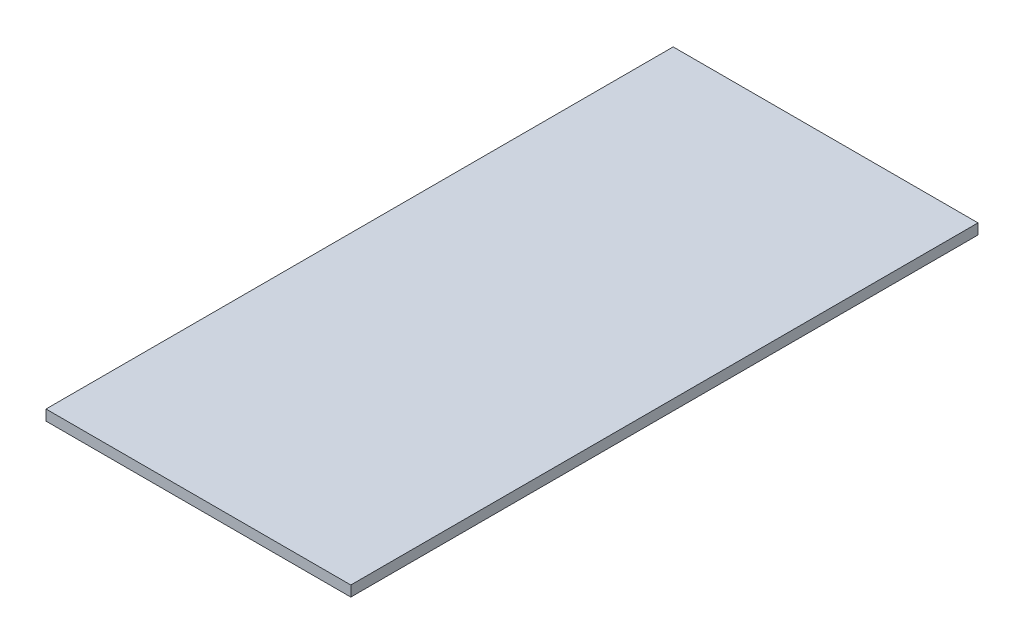
SolidWorks part; units mm, degrees
material "Pine"
ref_plane "Front Plane" through (0, 0, 0) normal (0, 0, 1) x (1, 0, 0)
ref_plane "Top Plane" through (0, 0, 0) normal (0, 1, 0) x (1, 0, 0)
ref_plane "Right Plane" through (0, 0, 0) normal (1, 0, 0) x (0, 0, -1)
sketch "Sketch2" plane through (0, 0, 0) normal (0, 1, 0) x (1, 0, 0)
  line L1 (-276.225, -568.3695) -> (276.225, -568.3695)
  line L2 (-276.225, -568.3695) -> (-276.225, 568.3695)
  line L3 (-276.225, 568.3695) -> (276.225, 568.3695)
  line L4 (276.225, -568.3695) -> (276.225, 568.3695)
  line L5 (-276.225, -568.3695) -> (276.225, 568.3695) construction
  line L6 (-276.225, 568.3695) -> (276.225, -568.3695) construction
  point P0 (0, 0)
  dimension "D1" = 552.45
  dimension "D2" = 1136.7389
extrude "Boss-Extrude1" add sketch "Sketch2" along normal blind 19.05
